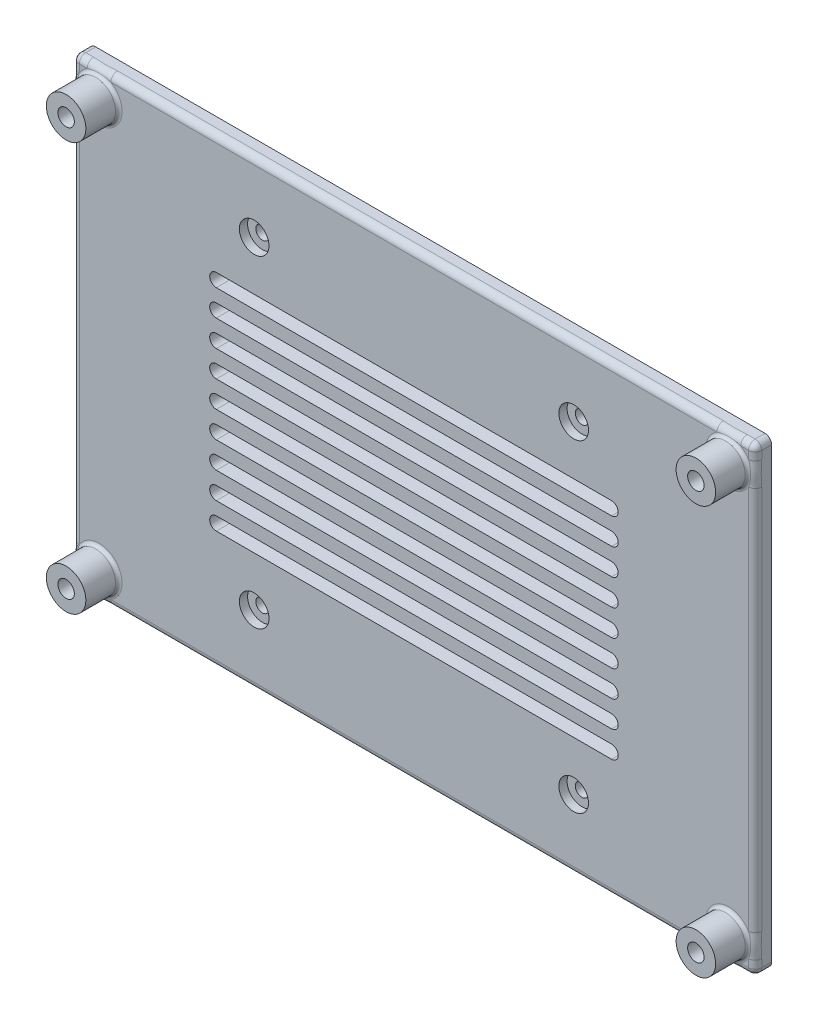
SolidWorks part; units mm, degrees
ref_plane "Plan de face" through (0, 0, 0) normal (0, 0, 1) x (1, 0, 0)
ref_plane "Plan de dessus" through (0, 0, 0) normal (0, 1, 0) x (1, 0, 0)
ref_plane "Plan de droite" through (0, 0, 0) normal (1, 0, 0) x (0, 0, -1)
sketch "Esquisse1" plane through (0, 0, 0) normal (0, 0, 1) x (1, 0, 0)
  line L1 (-51.8, 35) -> (51.8, 35)
  line L2 (-51.8, 35) -> (-51.8, -35)
  line L3 (-51.8, -35) -> (51.8, -35)
  line L4 (51.8, 35) -> (51.8, -35)
  line L5 (-51.8, 35) -> (51.8, -35) construction
  line L6 (-51.8, -35) -> (51.8, 35) construction
  line L7 (24.25, -24.5) -> (-24.25, -24.5) construction
  line L8 (24.25, -24.5) -> (24.25, 24.5) construction
  line L9 (24.25, 24.5) -> (-24.25, 24.5) construction
  line L10 (-24.25, -24.5) -> (-24.25, 24.5) construction
  line L11 (24.25, -24.5) -> (-24.25, 24.5) construction
  line L12 (24.25, 24.5) -> (-24.25, -24.5) construction
  circle A0 centre (-24.25, -24.5) radius 1.005
  circle A1 centre (-24.25, 24.5) radius 1.005
  circle A2 centre (24.25, -24.5) radius 1.005
  circle A3 centre (24.25, 24.5) radius 1.005
  point P0 (0, 0)
  point P5 (0, 0)
  point P13 (0, 0)
  dimension "D5" = 2.01
  dimension "D6" = 2.01
  dimension "D7" = 2.01
  dimension "D8" = 2.01
  dimension "D1" = 70
  dimension "D2" = 103.6
  dimension "D3" = 48.5
  dimension "D4" = 49
extrude "Boss.-Extru.1" add sketch "Esquisse1" along normal blind 2.5
sketch "Esquisse3" plane through (0, 0, 2.5) normal (0, 0, 1) x (1, 0, 0)
  line L0 (51.8, 35) -> (-51.8, 35) construction
  line L1 (-51.8, 35) -> (-51.8, -35) construction
  line L2 (-51.8, -35) -> (51.8, -35) construction
  line L3 (51.8, -35) -> (51.8, 35) construction
  circle A0 centre (-47.8, 31) radius 3
  circle A1 centre (47.8, 31) radius 3
  circle A2 centre (-47.8, -31) radius 3
  circle A3 centre (47.8, -31) radius 3
  point P17 (-47.8, 31)
  point P18 (-47.8, -31)
  point P19 (47.8, -31)
  point P20 (47.8, 31)
  dimension "D3" = 4
  dimension "D1" = 4
  dimension "D2" = 4
  dimension "D4" = 4
  dimension "D5" = 4
  dimension "D6" = 4
  dimension "D7" = 4
  dimension "D8" = 4
extrude "Boss.-Extru.2" add sketch "Esquisse3" along normal blind 5 contours A1 | A3 | A2 | A0
fillet "Congé2" radius 0.5 4 edges at (50.8, 31, 2.5) (50.8, -31, 2.5) (-44.8, -31, 2.5) (-44.8, 31, 2.5)
hole_wizard "Trou pour taraudage pour trou taraudé M32" positions "Esquisse15" profile "Esquisse16" hole size "M3" standard "AS"
sketch "Esquisse15" plane through (0, 0, 7.5) normal (0, 0, 1) x (1, 0, 0)
  point P0 (-47.8, -31)
  point P3 (47.8, -31)
  point P6 (47.8, 31)
  point P9 (-47.8, 31)
sketch "Esquisse16" plane through (-47.8, -31, 7.5) normal (1, 0, 0) x (0, -1, 0)
  line L0 (0, 0) -> (0, 5.7511)
  line L1 (0, 5.7511) -> (1.25, 5)
  line L2 (1.25, 5) -> (1.25, 0)
  line L5 (1.25, 0) -> (0, 0)
  line L10 (0, 5.7511) -> (-1.25, 5) construction
  line L11 (0, -6.35) -> (0, 107.95) construction
  dimension "Diamètre du perçage" = 2.5
  dimension "Profondeur du perçage" = 5
  dimension "Angle de pointe" = 118
sketch "Esquisse19" plane through (0, 0, 2.5) normal (0, 0, 1) x (1, 0, 0)
  circle A0 centre (24.25, -24.5) radius 2.25
  circle A1 centre (-24.25, -24.5) radius 2.25
  circle A2 centre (-24.25, 24.5) radius 2.25
  circle A3 centre (24.25, 24.5) radius 2.25
extrude "Enlèv. mat.-Extru.1" cut sketch "Esquisse19" against normal blind 1.25 contours A1 | A2 | A3 | A0
fillet "Congé3" radius 1 8 edges at (-51.8, 0, 2.5) (0, -35, 2.5) (0, 35, 2.5) (51.8, 0, 2.5) (51.8, -35, 1.25) (51.8, 35, 1.25) (-51.8, 35, 1.25) (-51.8, -35, 1.25)
sketch "Esquisse22" plane through (0, 0, 2.5) normal (0, 0, 1) x (1, 0, 0)
  line L0 (30, 0) -> (-30, 0) construction
  line L1 (30, -1) -> (-30, -1)
  line L2 (30, 1) -> (-30, 1)
  arc A0 (30, -1) -> (30, 1) centre (30, 0) ccw
  arc A1 (-30, 1) -> (-30, -1) centre (-30, 0) ccw
  point P2 (0, 0)
extrude "Enlèv. mat.-Extru.3" cut sketch "Esquisse22" against normal through all
pattern_linear "Répétition linéaire2" count 5 spacing 4 along (0, 1, 0) count 5 spacing 4 along (0, -1, 0) of "Enlèv. mat.-Extru.3"
